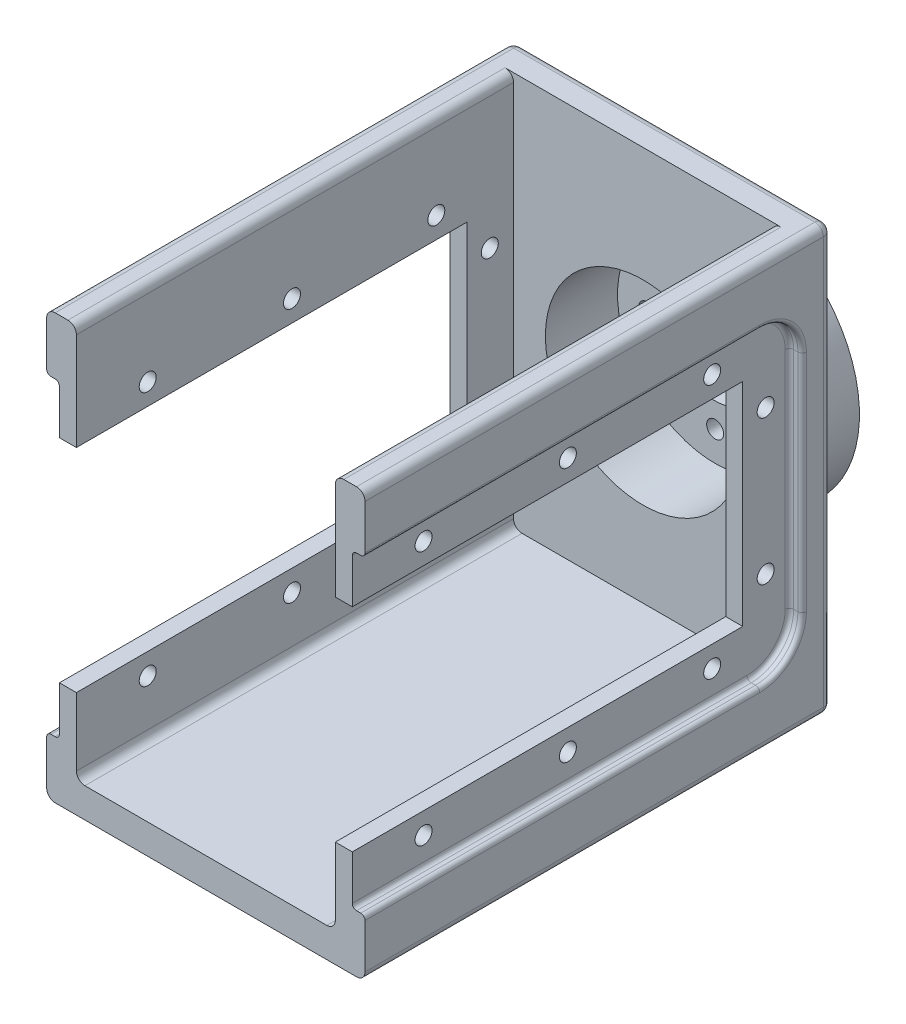
SolidWorks part; units mm, degrees
ref_plane "Front Plane" through (0, 0, 0) normal (0, 0, 1) x (1, 0, 0)
ref_plane "Top Plane" through (0, 0, 0) normal (0, 1, 0) x (1, 0, 0)
ref_plane "Right Plane" through (0, 0, 0) normal (1, 0, 0) x (0, 0, -1)
sketch "Sketch1" plane through (0, 0, 0) normal (0, 0, 1) x (1, 0, 0)
  line L1 (18.75, 25) -> (-18.75, 25)
  line L2 (18.75, 25) -> (18.75, -25)
  line L3 (18.75, -25) -> (-18.75, -25)
  line L4 (-18.75, 25) -> (-18.75, -25)
  point P4 (18.75, 0)
  point P7 (0, -25)
  dimension "D1" = 50
  dimension "D2" = 37.5
extrude "Boss-Extrude1" add sketch "Sketch1" along normal blind 55
sketch "Sketch3" plane through (0, 0, 0) normal (0, 0, -1) x (-1, 0, 0)
  line L0 (18.75, 0) -> (-18.75, 0) construction
  line L1 (18.75, 25) -> (18.75, -25) construction
  line L2 (-18.75, -25) -> (-18.75, 25) construction
  circle A0 centre (0, 0) radius 15
  dimension "D1" = 30
extrude "Boss-Extrude2" add sketch "Sketch3" along normal blind 7
shell "Shell1" thickness 3.5
sketch "Sketch4" plane through (0, 0, -3.5) normal (0, 0, 1) x (1, 0, 0)
  circle A0 centre (0, 0) radius 5.1215
  circle A2 centre (0, 0) radius 5.1215 construction
extrude "Cut-Extrude1" cut sketch "Sketch4" against normal blind 7
sketch "Sketch5" plane through (-18.75, 0, 0) normal (-1, 0, 0) x (0, 0, 1)
  line L1 (55, 12.5) -> (9, 12.5)
  line L2 (55, 12.5) -> (55, -12.5)
  line L3 (55, -12.5) -> (9, -12.5)
  line L4 (9, 12.5) -> (9, -12.5)
  line L5 (55, 25) -> (55, -25) construction
  point P7 (55, 0)
  point P8 (55, 0)
  dimension "D1" = 25
  dimension "D2" = 46
extrude "Cut-Extrude2" cut sketch "Sketch5" against normal through all both and the other way through all
sketch "Sketch6" plane through (18.75, 0, 0) normal (1, 0, 0) x (0, 0, -1)
  point P0 (-46.6, 15)
  point P1 (-29.6, 15)
  point P3 (-29.6, -15)
  point P5 (-46.6, -15)
  point P7 (-12.6, -15)
  point P9 (-6.3, -8.5)
  point P11 (-6.3, 8.5)
  point P13 (-12.6, 15)
hole_wizard "Tap Drill for M2 Tap1" positions "3DSketch1" profile "Sketch7" hole size "M2" standard "ISO" end condition through all
sketch3d "3DSketch1"
  point P0 (18.75, 15, 46.6)
  point P3 (18.75, 15, 29.6)
  point P6 (18.75, -15, 46.6)
  point P9 (18.75, -15, 29.6)
  point P12 (18.75, -15, 12.6)
  point P15 (18.75, -8.5, 6.3)
  point P18 (18.75, 8.5, 6.3)
  point P21 (18.75, 15, 12.6)
sketch "Sketch7" plane through (18.75, 15, 46.6) normal (0, 1, 0) x (0, 0, -1)
  line L0 (0, 0) -> (0, 37.5)
  line L1 (0, 37.5) -> (1, 37.5)
  line L2 (1, 37.5) -> (1, 0)
  line L5 (1, 0) -> (0, 0)
  line L11 (0, -6.35) -> (0, 107.95) construction
  dimension "Thru Hole Dia." = 2
  dimension "Thru Hole Depth" = 37.5
sketch "Sketch10" plane through (18.75, 0, 0) normal (1, 0, 0) x (0, 0, -1)
  line L0 (-55, -25) -> (-55, -12.5) construction
  line L1 (-55, -18.25) -> (-8.5, -18.25)
  line L2 (-55, -18.25) -> (-55, 18.25)
  line L3 (-55, 18.25) -> (-8.5, 18.25)
  line L4 (-3.5, -13.25) -> (-3.5, 13.25)
  arc A0 (-8.5, -18.25) -> (-3.5, -13.25) centre (-8.5, -13.25) ccw
  arc A1 (-8.5, 18.25) -> (-3.5, 13.25) centre (-8.5, 13.25) cw
  point P6 (-3.5, 0)
  point P11 (-3.5, -18.25)
  point P14 (-3.5, 18.25)
  dimension "D3" = 5
  dimension "D1" = 36.5
  dimension "D2" = 51.5
extrude "Cut-Extrude4" cut sketch "Sketch10" against normal blind 1.5
mirror "Mirror1" about plane through (0, 0, 0) normal (1, 0, 0) of "Cut-Extrude4"
fillet "Fillet1" radius 1 13 edges at (-15.25, -21.5, 29.25) (15.25, -21.5, 29.25) (-18.75, -25, 27.5) (18.75, -25, 27.5) (15.25, 25, 29.25) (-18.75, 25, 27.5) (0, -25, 0) (-15.25, 25, 29.25) (18.75, 25, 27.5) (18.75, 0, 0) (-18.75, 0, 0) (0, 25, 0) (-15, 0, 0)
fillet "Fillet2" radius 0.5 20 edges at (17.25, -18.25, 31.75) (18.75, -18.25, 31.75) (17.25, 0, 3.5) (18.75, 0, 3.5) (18.75, 18.25, 31.75) (17.25, 18.25, 31.75) (-17.25, 0, 3.5) (-18.75, 0, 3.5) (-18.75, 18.25, 31.75) (-18.75, -18.25, 31.75) (-17.25, -18.25, 31.75) (-17.25, 18.25, 31.75) (18.75, -16.7855, 4.9645) (18.75, 16.7855, 4.9645) (17.25, -16.7855, 4.9645) (17.25, 16.7855, 4.9645) (-18.75, 16.7855, 4.9645) (-18.75, -16.7855, 4.9645) (-17.25, -16.7855, 4.9645) (-17.25, 16.7855, 4.9645)
sketch "Sketch11" plane through (0, 0, -3.5) normal (0, 0, 1) x (1, 0, 0)
  circle A1 centre (0, 0) radius 11.5
  circle A2 centre (0, 0) radius 11.5
  dimension "D1" = 0
extrude "Cut-Extrude5" cut sketch "Sketch11" against normal blind 1.5
sketch "Sketch13" plane through (0, 0, -5) normal (0, 0, 1) x (1, 0, 0)
  point P0 (0, 8)
  point P1 (5.6569, 5.6569)
  point P3 (8, 0)
  point P5 (5.6569, -5.6569)
  point P7 (0, -8)
  point P9 (-5.6569, -5.6569)
  point P11 (-8, 0)
  point P13 (-5.6569, 5.6569)
hole_wizard "Ø1.0mm Dowel Hole1" positions "3DSketch3" profile "Sketch16" hole size "Ø1.0" standard "ISO" end condition through all
sketch3d "3DSketch3"
  point P0 (5.6569, 5.6569, -5)
  point P3 (0, 8, -5)
  point P6 (8, 0, -5)
  point P9 (5.6569, -5.6569, -5)
  point P12 (0, -8, -5)
  point P15 (-5.6569, -5.6569, -5)
  point P18 (-8, 0, -5)
  point P21 (-5.6569, 5.6569, -5)
sketch "Sketch16" plane through (5.6569, 5.6569, -5) normal (1, 0, 0) x (0, -1, 0)
  line L0 (0, 0) -> (0, 2)
  line L1 (0, 2) -> (1, 2)
  line L2 (1, 2) -> (1, 0)
  line L5 (1, 0) -> (0, 0)
  line L11 (0, -6.35) -> (0, 107.95) construction
  dimension "Thru Hole Dia." = 2
  dimension "Thru Hole Depth" = 2
